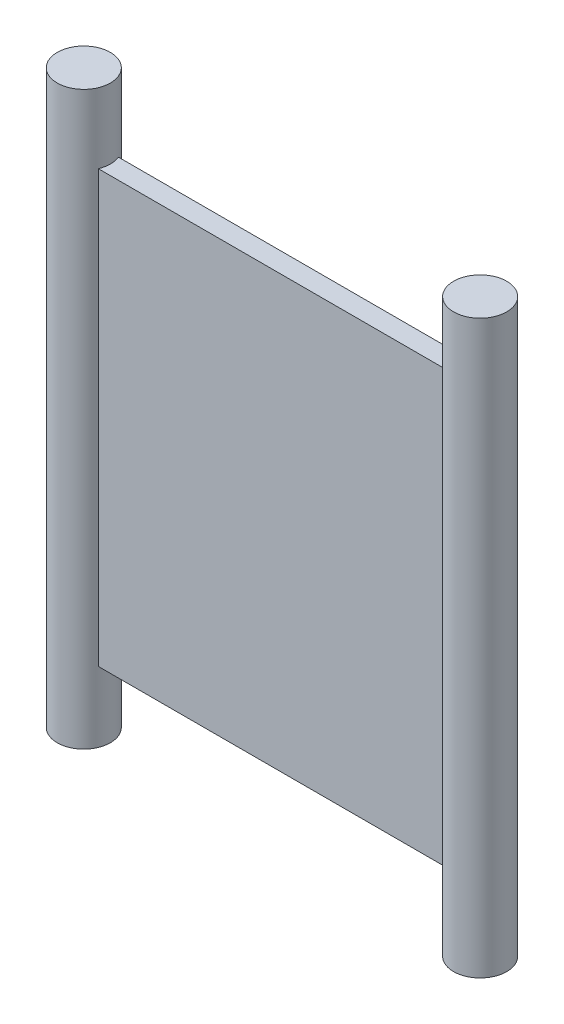
SolidWorks part; units mm, degrees
ref_plane "Front Plane" through (0, 0, 0) normal (0, 0, 1) x (1, 0, 0)
ref_plane "Top Plane" through (0, 0, 0) normal (0, 1, 0) x (1, 0, 0)
ref_plane "Right Plane" through (0, 0, 0) normal (1, 0, 0) x (0, 0, -1)
sketch "Sketch1" plane through (0, 0, 0) normal (0, 1, 0) x (1, 0, 0)
  line L1 (9.885, 0.5) -> (-9.885, 0.5)
  line L2 (9.885, 0.5) -> (9.885, -0.5)
  line L3 (9.885, -0.5) -> (-9.885, -0.5)
  line L4 (-9.885, 0.5) -> (-9.885, -0.5)
  line L5 (9.885, 0.5) -> (-9.885, -0.5) construction
  line L6 (9.885, -0.5) -> (-9.885, 0.5) construction
  point P0 (0, 0)
  dimension "D1" = 19.77
  dimension "D3" = 1
extrude "Boss-Extrude1" add sketch "Sketch1" along normal blind 21.5
ref_plane "Plane1" through (0, 10.75, 0) normal (0, 1, 0) x (1, 0, 0)
sketch "Sketch2" plane through (0, 10.75, 0) normal (0, 1, 0) x (1, 0, 0)
  line L0 (9.885, -0.5) -> (9.885, 0.5) construction
  line L1 (-9.885, 0.5) -> (-9.885, -0.5) construction
  line L2 (9.885, -0.5) -> (9.885, 0.5) construction
  line L3 (-9.885, 0.5) -> (-9.885, -0.5) construction
  circle A0 centre (-9.885, 0) radius 1.325
  circle A1 centre (9.885, 0) radius 1.325
  dimension "D1" = 2.65
extrude "Boss-Extrude2" add sketch "Sketch2" along normal mid plane 28.5
